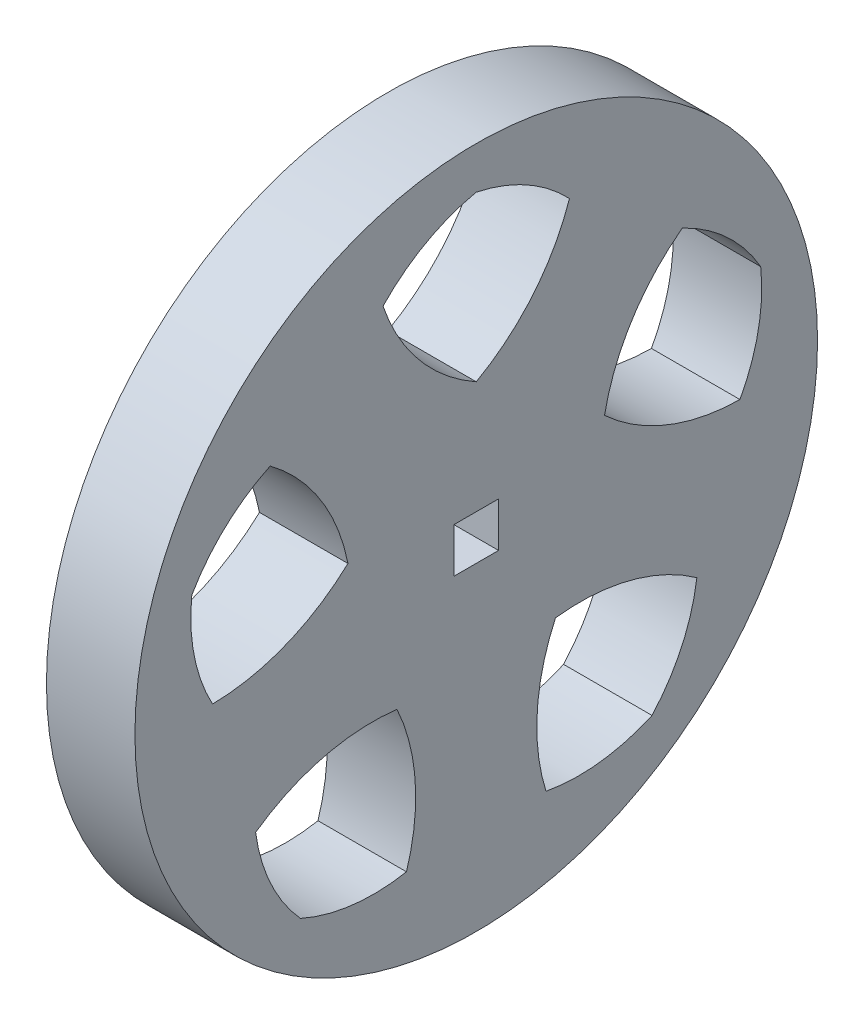
SolidWorks part; units mm, degrees
ref_plane "Front Plane" through (0, 0, 0) normal (0, 0, 1) x (1, 0, 0)
ref_plane "Top Plane" through (0, 0, 0) normal (0, 1, 0) x (1, 0, 0)
ref_plane "Right Plane" through (0, 0, 0) normal (1, 0, 0) x (0, 0, -1)
sketch "Sketch1" plane through (0, 0, 0) normal (1, 0, 0) x (0, 0, -1)
  circle A0 centre (0, 0) radius 13.5
  dimension "D1" = 27
extrude "Boss-Extrude1" add sketch "Sketch1" along normal blind 3.5
sketch "Sketch2" plane through (0, 0, 0) normal (1, 0, 0) x (0, 0, -1)
  line L0 (0, 0) -> (0, 14.8201) construction
  arc A0 (0, 5.3352) -> (-3.6873, 9.769) centre (3.9038, 12.3319) cw
  arc A1 (-3.6873, 9.769) -> (0, 11.8295) centre (1.4581, 4.8907) cw
  arc A2 (3.6873, 9.769) -> (0, 11.8295) centre (-1.4581, 4.8907) ccw
  arc A3 (0, 5.3352) -> (3.6873, 9.769) centre (-3.9038, 12.3319) ccw
  point P11 (-3.9038, 9.769)
  point P12 (0, 11.8295)
extrude "Cut-Extrude1" cut sketch "Sketch2" along normal up to next
pattern_circular "CirPattern1" count 5 over 360 about axis through (0, 0, 0) along (1, 0, 0) of "Cut-Extrude1"
sketch "Sketch3" plane through (0, 0, 0) normal (1, 0, 0) x (0, 0, -1)
  line L1 (0.8839, -0.8839) -> (-0.8839, -0.8839)
  line L2 (0.8839, -0.8839) -> (0.8839, 0.8839)
  line L3 (0.8839, 0.8839) -> (-0.8839, 0.8839)
  line L4 (-0.8839, -0.8839) -> (-0.8839, 0.8839)
  line L5 (0.8839, -0.8839) -> (-0.8839, 0.8839) construction
  line L6 (0.8839, 0.8839) -> (-0.8839, -0.8839) construction
  circle A0 centre (0, 0) radius 1.25 construction
  dimension "D1" = 2.5
extrude "Cut-Extrude2" cut sketch "Sketch3" along normal up to next
